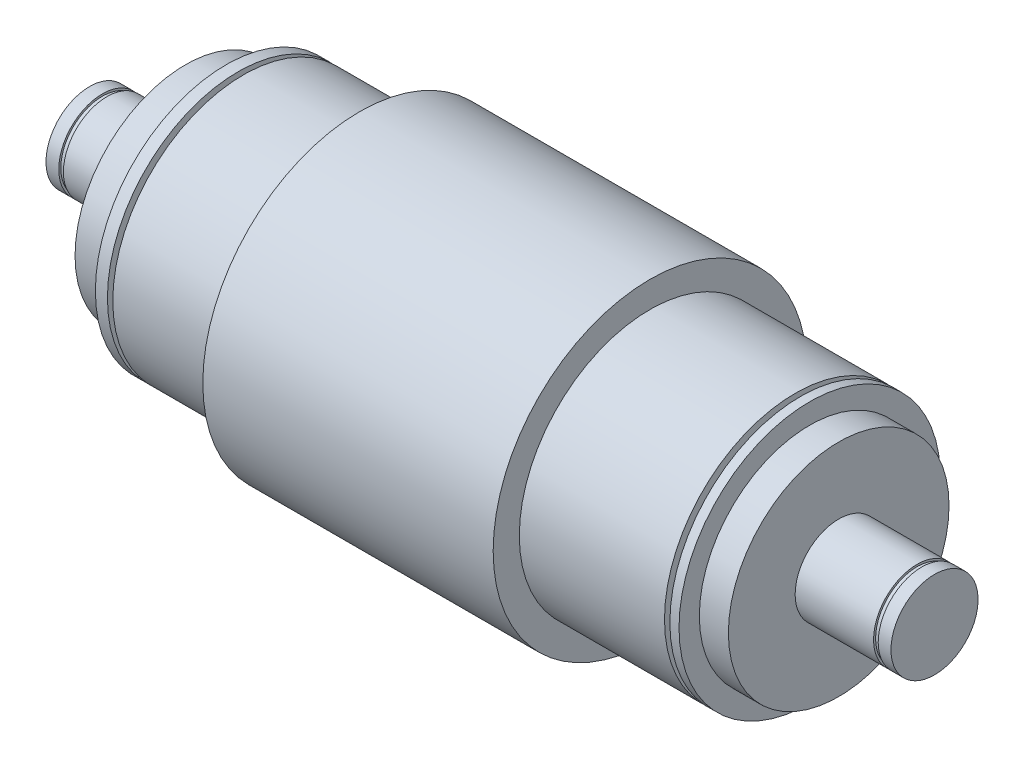
SolidWorks part; units mm, degrees
ref_plane "Piano frontale" through (0, 0, 0) normal (0, 0, 1) x (1, 0, 0)
ref_plane "Piano superiore" through (0, 0, 0) normal (0, 1, 0) x (1, 0, 0)
ref_plane "Piano destro" through (0, 0, 0) normal (1, 0, 0) x (0, 0, -1)
sketch "Schizzo1" plane through (0, 0, 0) normal (0, 0, 1) x (1, 0, 0)
  line L0 (0, 0) -> (291, 0)
  line L1 (0, 0) -> (0, 15)
  line L2 (0, 15) -> (33, 15)
  line L3 (33, 15) -> (33, 38)
  line L4 (33, 38) -> (47, 38)
  line L5 (47, 38) -> (47, 45)
  line L6 (47, 45) -> (93, 45)
  line L7 (93, 45) -> (93, 54)
  line L8 (93, 54) -> (193, 54)
  line L9 (193, 54) -> (193, 45)
  line L10 (193, 45) -> (248, 45)
  line L11 (248, 45) -> (248, 38)
  line L12 (248, 38) -> (258, 38)
  line L13 (258, 38) -> (258, 15)
  line L14 (258, 15) -> (291, 15)
  line L15 (291, 15) -> (291, 0)
  dimension "D1" = 291
  dimension "D2" = 33
  dimension "D3" = 47
  dimension "D4" = 93
  dimension "D5" = 15
  dimension "D6" = 38
  dimension "D7" = 45
  dimension "D8" = 54
  dimension "D9" = 98
  dimension "D10" = 43
  dimension "D11" = 33
revolve "Rivoluzione1" add sketch "Schizzo1" angle 360 about L0
sketch "Schizzo2" plane through (0, 0, 0) normal (0, 0, 1) x (1, 0, 0)
  line L0 (0, 0) -> (291, 0) construction
  line L1 (291, -15) -> (291, 15) construction
  line L2 (33, 15) -> (0, 15) construction
  line L3 (4.4, 15) -> (6, 15)
  line L4 (4.4, 15) -> (4.4, 14.3)
  line L5 (4.4, 14.3) -> (6, 14.3)
  line L6 (6, 15) -> (6, 14.3)
  line L7 (93, 45) -> (47, 45) construction
  line L8 (51.15, 45) -> (53, 45)
  line L9 (51.15, 45) -> (51.15, 21.25)
  line L10 (51.15, 21.25) -> (53, 21.25)
  line L11 (53, 45) -> (53, 21.25)
  line L12 (248, 45) -> (193, 45) construction
  line L13 (243, 45) -> (244.85, 45)
  line L14 (243, 45) -> (243, 21.25)
  line L15 (243, 21.25) -> (244.85, 21.25)
  line L16 (244.85, 45) -> (244.85, 21.25)
  line L17 (291, 15) -> (258, 15) construction
  line L18 (285, 15) -> (286.6, 15)
  line L19 (285, 15) -> (285, 14.3)
  line L20 (285, 14.3) -> (286.6, 14.3)
  line L21 (286.6, 15) -> (286.6, 14.3)
  line L22 (33, 15) -> (33, -15) construction
  line L23 (93, 54) -> (93, -54) construction
  line L24 (193, -54) -> (193, 54) construction
  line L25 (258, -38) -> (258, 38) construction
  point P31 (5.2, 14.3)
  dimension "D1" = 1.6
  dimension "D2" = 27
  dimension "D3" = 14.3
  dimension "D4" = 1.85
  dimension "D5" = 40
  dimension "D6" = 21.25
  dimension "D7" = 50
  dimension "D8" = 27
revolve "Taglia-Rivoluzione1" cut sketch "Schizzo2" angle 360 about L0
